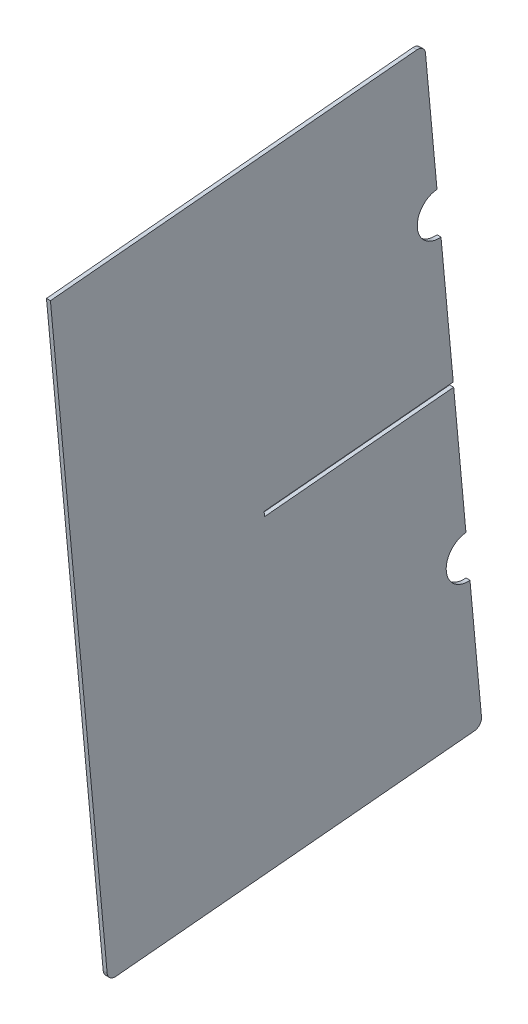
SolidWorks part; units mm, degrees
ref_plane "前视基准面" through (0, 0, 0) normal (0, 0, 1) x (1, 0, 0)
ref_plane "上视基准面" through (0, 0, 0) normal (0, 1, 0) x (1, 0, 0)
ref_plane "右视基准面" through (0, 0, 0) normal (1, 0, 0) x (0, 0, -1)
ref_plane "基准面1" through (-61.5, 0, 0) normal (-1, 0, 0) x (0, -1, 0)
sketch "草图1" plane through (-61.5, 0, 0) normal (-1, 0, 0) x (0, -1, 0)
  line L0 (145.113, 800.6032) -> (176.3784, 797.6987)
  line L1 (178.5548, 799.5051) -> (187.1573, 892.1064)
  line L2 (187.1573, 892.1064) -> (-47.8309, 913.9365)
  line L3 (-47.8309, 913.9365) -> (-56.4334, 821.3352)
  line L4 (-54.627, 819.1588) -> (-23.3616, 816.2543)
  line L5 (-12.4088, 815.2368) -> (20.8481, 812.1473)
  line L6 (20.8481, 812.1473) -> (25.2881, 859.9415)
  line L7 (25.2881, 859.9415) -> (26.4829, 859.8305)
  line L8 (26.4829, 859.8305) -> (22.0429, 812.0363)
  line L9 (22.0429, 812.0363) -> (55.3993, 808.9375)
  line L10 (66.3521, 807.92) -> (99.7085, 804.8212)
  line L11 (99.7085, 804.8212) -> (104.1485, 852.6154)
  line L12 (104.1485, 852.6154) -> (105.3434, 852.5044)
  line L13 (105.3434, 852.5044) -> (100.9033, 804.7102)
  line L14 (100.9033, 804.7102) -> (134.1602, 801.6207)
  arc A0 (176.3784, 797.6987) -> (178.5548, 799.5051) centre (176.5634, 799.6901) ccw
  arc A1 (-56.4334, 821.3352) -> (-54.627, 819.1588) centre (-54.442, 821.1502) ccw
  arc A2 (-23.3616, 816.2543) -> (-12.4088, 815.2368) centre (-17.8852, 815.7455) cw
  arc A3 (55.3993, 808.9375) -> (66.3521, 807.92) centre (60.8757, 808.4287) cw
  arc A4 (134.1602, 801.6207) -> (145.113, 800.6032) centre (139.6366, 801.112) cw
extrude "凸台-拉伸1" add sketch "草图1" against normal blind 1
sketch "草图2" plane through (-60.5, 0, 0) normal (1, 0, 0) x (0, 0, -1)
  line L0 (-804.8212, -99.7085) -> (-899.4139, -108.496)
  line L1 (-892.1064, -187.1573) -> (-913.9365, 47.8309) construction
  line L2 (-899.4139, -108.496) -> (-892.1064, -187.1573)
  line L3 (-892.1064, -187.1573) -> (-797.5137, -178.3698)
  line L4 (-797.5137, -178.3698) -> (-804.8212, -99.7085)
extrude "切除-拉伸1" cut sketch "草图2" against normal blind 10
fillet "圆角1" radius 2 1 edges at (-61, -108.496, 899.4139)
fillet "圆角2" radius 2 1 edges at (-61, -99.7085, 804.8212)
